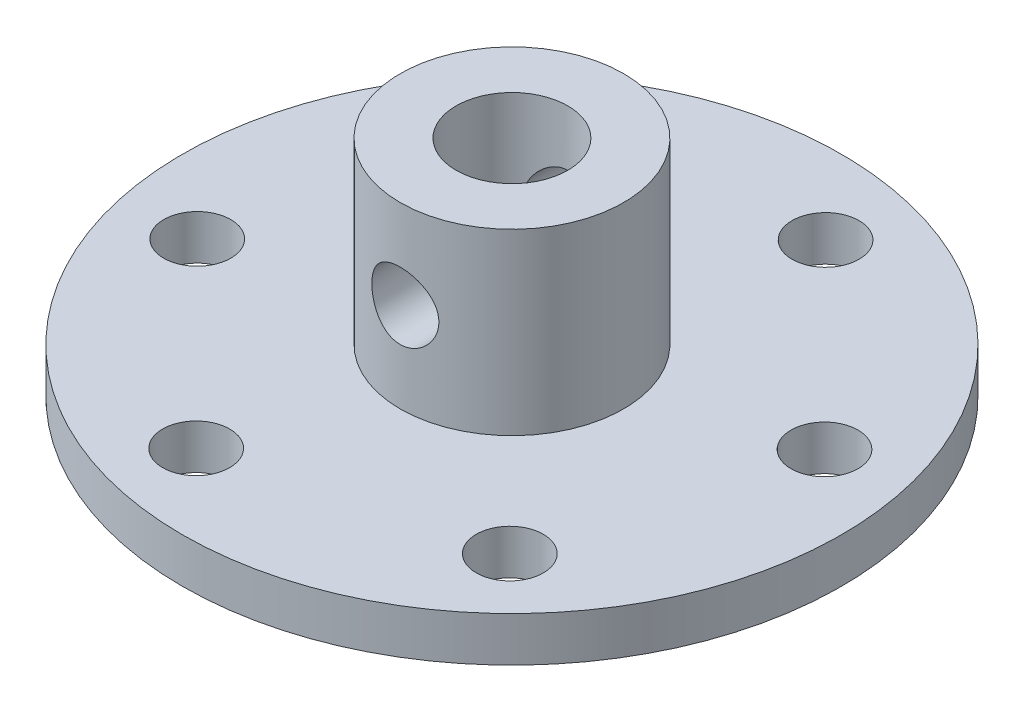
SolidWorks part; units mm, degrees
ref_plane "Front Plane" through (0, 0, 0) normal (0, 0, 1) x (1, 0, 0)
ref_plane "Top Plane" through (0, 0, 0) normal (0, 1, 0) x (1, 0, 0)
ref_plane "Right Plane" through (0, 0, 0) normal (1, 0, 0) x (0, 0, -1)
sketch "Sketch1" plane through (0, 0, 0) normal (0, 1, 0) x (1, 0, 0)
  line L0 (0, 29.5) -> (0, -29.5) construction
  line L1 (-29.5, 0) -> (29.5, 0) construction
  line L2 (-20.8597, -20.8597) -> (20.8597, 20.8597) construction
  line L3 (-20.8597, 20.8597) -> (20.8597, -20.8597) construction
  circle A0 centre (0, 0) radius 29.5
  circle A1 centre (-16.2635, 16.2635) radius 3
  circle A2 centre (5.9328, 22.1416) radius 3
  circle A3 centre (22.1216, 5.8581) radius 3
  circle A4 centre (16.1141, -16.3035) radius 3
  circle A5 centre (-6.0822, -22.1816) radius 3
  circle A6 centre (-22.271, -5.8982) radius 3
  point P26 (-0.0747, -0.02)
  dimension "D1" = 59
  dimension "D2" = 6
  dimension "D3" = 135
  dimension "D4" = 45
  dimension "D6" = 23
  dimension "D5" = 6
extrude "Boss-Extrude1" add sketch "Sketch1" along normal blind 4
sketch "Sketch2" plane through (0, 4, 0) normal (0, 1, 0) x (1, 0, 0)
  circle A0 centre (0, 0) radius 10
  circle A1 centre (0, 0) radius 5
  dimension "D1" = 20
  dimension "D2" = 10
extrude "Boss-Extrude2" add sketch "Sketch2" along normal blind 16
sketch "Sketch3" plane through (0, 0, 0) normal (0, 0, 1) x (1, 0, 0)
  circle A0 centre (0, 12) radius 3
  dimension "D1" = 6
  dimension "D2" = 12
extrude "Cut-Extrude1" cut sketch "Sketch3" against normal mid plane 26
